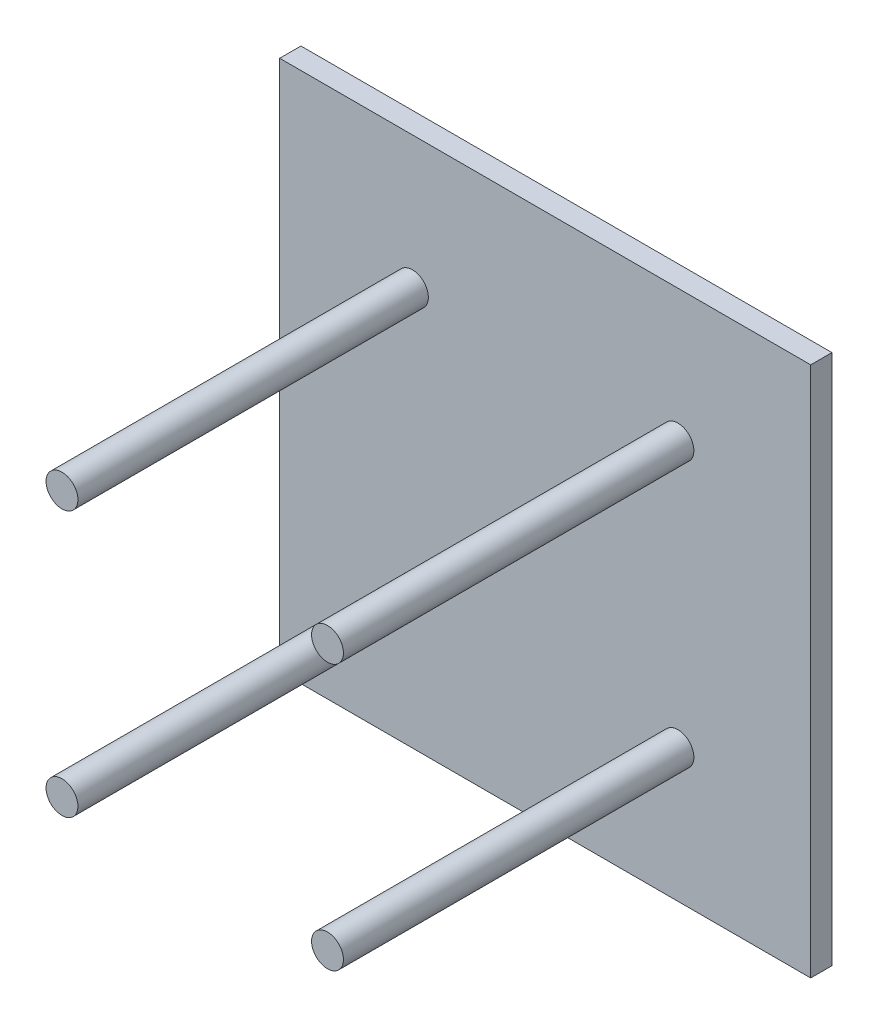
SolidWorks part; units mm, degrees
ref_plane "前视基准面" through (0, 0, 0) normal (0, 0, 1) x (1, 0, 0)
ref_plane "上视基准面" through (0, 0, 0) normal (0, 1, 0) x (1, 0, 0)
ref_plane "右视基准面" through (0, 0, 0) normal (1, 0, 0) x (0, 0, -1)
other "Configuration Table"
sketch "草图1" plane through (0, 0, 0) normal (0, 0, 1) x (1, 0, 0)
  line L1 (-500, -500) -> (500, -500)
  line L2 (-500, -500) -> (-500, 500)
  line L3 (-500, 500) -> (500, 500)
  line L4 (500, -500) -> (500, 500)
  line L5 (-500, -500) -> (500, 500) construction
  line L6 (-500, 500) -> (500, -500) construction
  point P0 (0, 0)
extrude "凸台-拉伸1" add sketch "草图1" along normal blind 40
sketch "草图2" plane through (0, 0, 0) normal (0, 0, 1) x (1, 0, 0)
  circle A0 centre (-250, -250) radius 30
extrude "凸台-拉伸2" add sketch "草图2" along normal blind 700
sketch "草图3" plane through (0, 0, 0) normal (0, 0, 1) x (1, 0, 0)
  circle A0 centre (250, -250) radius 30
extrude "凸台-拉伸3" add sketch "草图3" along normal blind 700
sketch "草图4" plane through (0, 0, 0) normal (0, 0, 1) x (1, 0, 0)
  circle A0 centre (-250, 250) radius 30
extrude "凸台-拉伸4" add sketch "草图4" along normal blind 700
sketch "草图5" plane through (0, 0, 0) normal (0, 0, 1) x (1, 0, 0)
  circle A0 centre (250, 250) radius 30
extrude "凸台-拉伸5" add sketch "草图5" along normal blind 700
